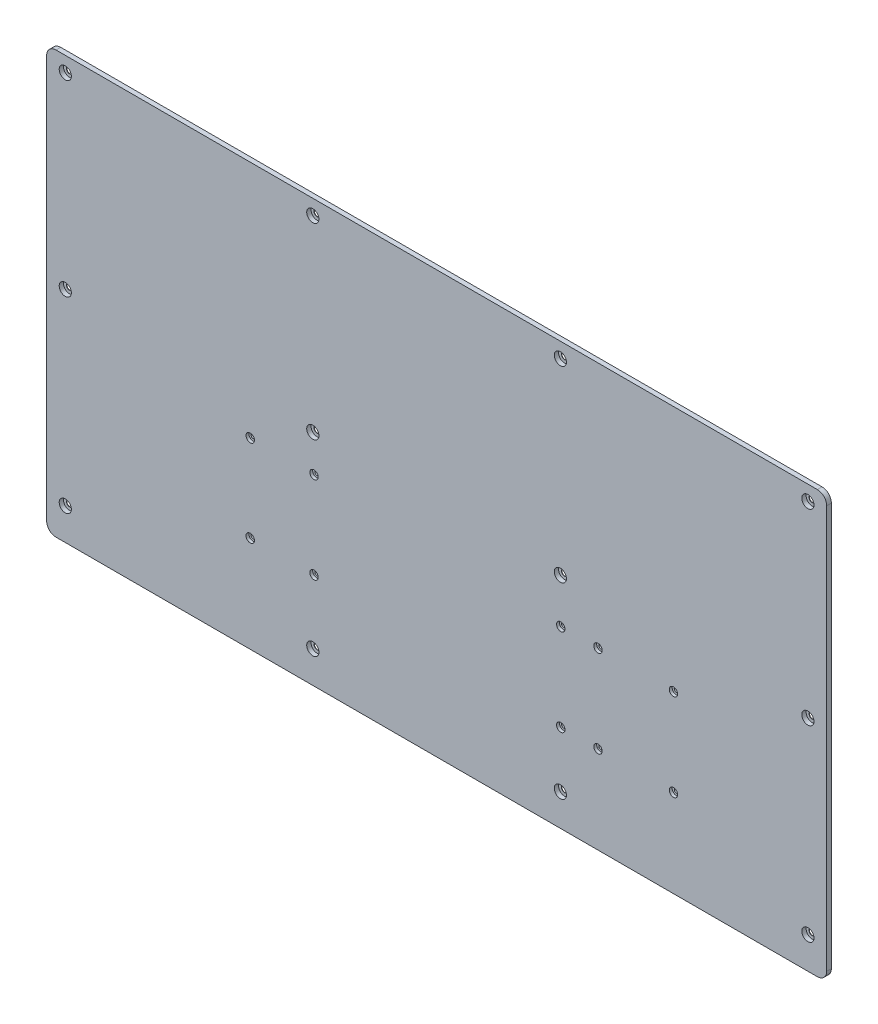
SolidWorks part; units mm, degrees
ref_plane "Plan de face" through (0, 0, 0) normal (0, 0, 1) x (1, 0, 0)
ref_plane "Plan de dessus" through (0, 0, 0) normal (0, 1, 0) x (1, 0, 0)
ref_plane "Plan de droite" through (0, 0, 0) normal (1, 0, 0) x (0, 0, -1)
sketch "Esquisse1" plane through (0, 0, 0) normal (0, 0, 1) x (1, 0, 0)
  line L1 (-406, -225) -> (406, -225)
  line L2 (-416, -215) -> (-416, 215)
  line L3 (-406, 225) -> (406, 225)
  line L4 (416, -215) -> (416, 215)
  line L5 (-416, -225) -> (416, 225) construction
  line L6 (-416, 225) -> (416, -225) construction
  arc A0 (416, 215) -> (406, 225) centre (406, 215) ccw
  arc A1 (406, -225) -> (416, -215) centre (406, -215) ccw
  arc A2 (-406, -225) -> (-416, -215) centre (-406, -215) cw
  arc A3 (-416, 215) -> (-406, 225) centre (-406, 215) cw
  point P0 (0, 0)
  dimension "D3" = 10
  dimension "D1" = 832
  dimension "D2" = 450
extrude "Boss.-Extru.1" add sketch "Esquisse1" along normal blind 5
hole_wizard "Dégagement M61" positions "Esquisse3" profile "Esquisse2" hole size "M6" standard "JIS" end condition through all
sketch "Esquisse3" plane through (0, 0, 0) normal (0, 0, -1) x (-1, 0, 0)
  point P0 (-395.9198, 208.8724)
sketch "Esquisse2" plane through (395.9198, 208.8724, 0) normal (1, 0, 0) x (0, 1, 0)
  line L0 (0, 0) -> (0, 5)
  line L1 (0, 5) -> (3.3, 5)
  line L2 (3.3, 5) -> (3.3, 0)
  line L5 (3.3, 0) -> (0, 0)
  line L11 (0, -6.35) -> (0, 107.95) construction
  dimension "Diamètre du perçage jusqu'au prochain" = 6.6
  dimension "Profondeur du perçage jusqu'au prochain" = 5
hole_wizard "Chambrage pour vis à tête ronde bombée M61" positions "Esquisse5" profile "Esquisse4" counterbore size "M6" standard "Ansi Metric" end condition through all
sketch "Esquisse5" plane through (0, 0, 5) normal (0, 0, 1) x (1, 0, 0)
  point P0 (395.9198, 208.8724)
sketch "Esquisse4" plane through (395.9198, 208.8724, 5) normal (1, 0, 0) x (0, -1, 0)
  line L0 (0, 0) -> (0, 5)
  line L1 (0, 5) -> (3.3, 5)
  line L2 (3.3, 4.625) -> (3.3, 5)
  line L3 (3.3, 4.625) -> (3.325, 4.6)
  line L4 (3.325, 4.6) -> (6.5, 4.6)
  line L5 (6.5, 4.6) -> (6.5, 0)
  line L7 (0, 0) -> (6.5, 0)
  line L9 (-3.3, 4.625) -> (-3.325, 4.6) construction
  line L11 (0, -6.35) -> (0, 107.95) construction
  dimension "Diamètre du perçage jusqu'au prochain" = 6.6
  dimension "Profondeur du perçage jusqu'au prochain" = 5
  dimension "Diamètre du chambrage" = 13
  dimension "Profondeur du chambrage" = 4.6
  dimension "Diamètre du fraisage milieu" = 6.65
  dimension "Angle du fraisage milieu" = 90
pattern_linear "Répétition linéaire1" count 5 spacing 100 along (0, -1, 0) count 4 spacing 264 along (-1, 0, 0) skipping (1, 0), (1, 1), (1, 2), (1, 3), (3, 0), (3, 1), (3, 2), (3, 3) of "Chambrage pour vis à tête ronde bombée M61"
hole_wizard "Chambrage pour vis à tête ronde bombée M41" positions "Esquisse8" profile "Esquisse6" counterbore size "M4" standard "Ansi Metric" end condition through all
sketch "Esquisse8" plane through (0, 0, 5) normal (0, 0, 1) x (1, 0, 0)
  point P0 (132.3935, -131.4566)
  point P2 (172.0603, -131.4566)
  point P4 (252.5705, -131.4566)
sketch "Esquisse6" plane through (132.3935, -131.4566, 5) normal (1, 0, 0) x (0, -1, 0)
  line L0 (0, 0) -> (0, 5)
  line L1 (0, 5) -> (2.25, 5)
  line L2 (2.25, 3.125) -> (2.25, 5)
  line L3 (2.25, 3.125) -> (2.275, 3.1)
  line L4 (2.275, 3.1) -> (4.5, 3.1)
  line L5 (4.5, 3.1) -> (4.5, 0)
  line L7 (0, 0) -> (4.5, 0)
  line L9 (-2.25, 3.125) -> (-2.275, 3.1) construction
  line L11 (0, -6.35) -> (0, 107.95) construction
  dimension "Diamètre du perçage jusqu'au prochain" = 4.5
  dimension "Profondeur du perçage jusqu'au prochain" = 5
  dimension "Diamètre du chambrage" = 9
  dimension "Profondeur du chambrage" = 3.1
  dimension "Diamètre du fraisage milieu" = 4.55
  dimension "Angle du fraisage milieu" = 90
pattern_linear "Répétition linéaire2" count 2 spacing 93 along (0, 1, 0) of "Chambrage pour vis à tête ronde bombée M41"
hole_wizard "Chambrage pour vis à tête ronde bombée M42" positions "Esquisse10" profile "Esquisse9" counterbore size "M4" standard "Ansi Metric" end condition through all
sketch "Esquisse10" plane through (0, 0, 5) normal (0, 0, 1) x (1, 0, 0)
  point P0 (-130.8155, -122.2563)
  point P2 (-130.8155, -29.7118)
sketch "Esquisse9" plane through (-130.8155, -122.2563, 5) normal (1, 0, 0) x (0, -1, 0)
  line L0 (0, 0) -> (0, 5)
  line L1 (0, 5) -> (2.25, 5)
  line L2 (2.25, 3.125) -> (2.25, 5)
  line L3 (2.25, 3.125) -> (2.275, 3.1)
  line L4 (2.275, 3.1) -> (4.5, 3.1)
  line L5 (4.5, 3.1) -> (4.5, 0)
  line L7 (0, 0) -> (4.5, 0)
  line L9 (-2.25, 3.125) -> (-2.275, 3.1) construction
  line L11 (0, -6.35) -> (0, 107.95) construction
  dimension "Diamètre du perçage jusqu'au prochain" = 4.5
  dimension "Profondeur du perçage jusqu'au prochain" = 5
  dimension "Diamètre du chambrage" = 9
  dimension "Profondeur du chambrage" = 3.1
  dimension "Diamètre du fraisage milieu" = 4.55
  dimension "Angle du fraisage milieu" = 90
pattern_linear "Répétition linéaire3" count 2 spacing 68 along (-1, 0, 0) of "Chambrage pour vis à tête ronde bombée M42"
